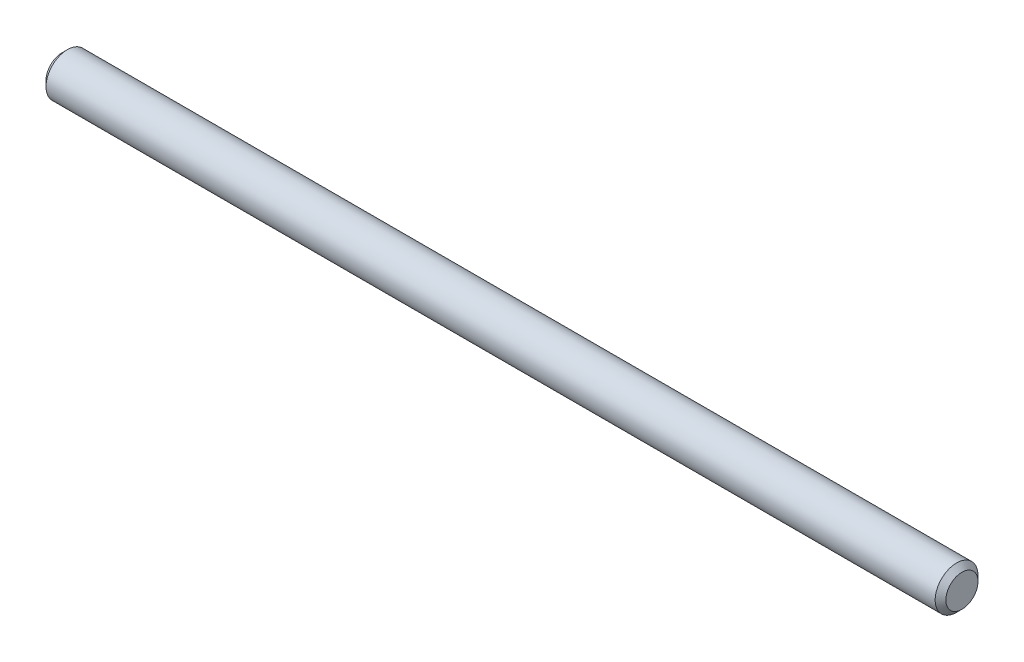
SolidWorks part; units mm, degrees
ref_plane "Front Plane" through (0, 0, 0) normal (0, 0, 1) x (1, 0, 0)
ref_plane "Top Plane" through (0, 0, 0) normal (0, 1, 0) x (1, 0, 0)
ref_plane "Right Plane" through (0, 0, 0) normal (1, 0, 0) x (0, 0, -1)
sketch "Sketch1" plane through (0, 0, 0) normal (1, 0, 0) x (0, 0, -1)
  circle A0 centre (0, 0) radius 2
  dimension "D1" = 4
extrude "Boss-Extrude1" add sketch "Sketch1" along normal mid plane 84
cosmetic thread "Cosmetic Thread1" parameters "D1"=8, "D2"=3.22
cosmetic thread "Cosmetic Thread2" parameters "D1"=8, "D2"=3.22
chamfer "Chamfer1" distance 0.5 angle 45 2 edges at (-42, 0, -2) (42, 0, -2)
